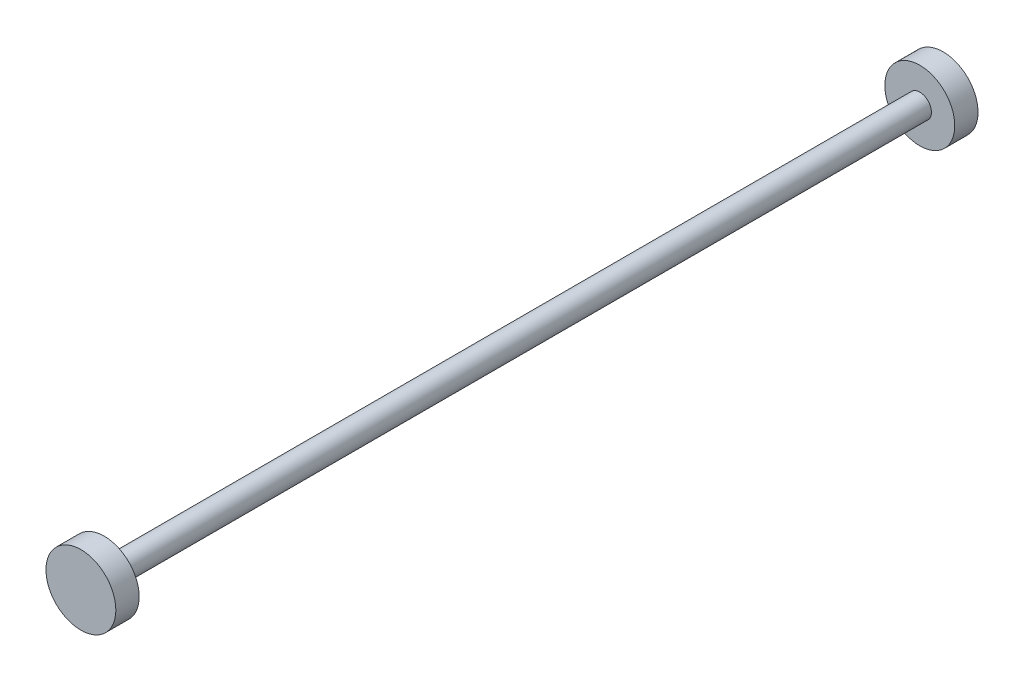
SolidWorks part; units mm, degrees
material "Pine"
ref_plane "Front Plane" through (0, 0, 0) normal (0, 0, 1) x (1, 0, 0)
ref_plane "Top Plane" through (0, 0, 0) normal (0, 1, 0) x (1, 0, 0)
ref_plane "Right Plane" through (0, 0, 0) normal (1, 0, 0) x (0, 0, -1)
sketch "Sketch1" plane through (0, 0, 0) normal (0, 0, 1) x (1, 0, 0)
  circle A0 centre (-12.2104, 19.4427) radius 12.7
  circle A1 centre (-12.2104, 19.4427) radius 38.1
extrude "Boss-Extrude2" add sketch "Sketch1" along normal blind 889 contours A0
sketch "Sketch4" plane through (0, 0, 889) normal (0, 0, 1) x (1, 0, 0)
  circle A0 centre (-12.2104, 19.4427) radius 38.1
extrude "Boss-Extrude4" add sketch "Sketch4" along normal blind 25.4
sketch "Sketch5" plane through (0, 0, 0) normal (0, 0, -1) x (-1, 0, 0)
  circle A0 centre (12.2104, 19.4427) radius 38.1
extrude "Boss-Extrude5" add sketch "Sketch5" along normal blind 25.4
